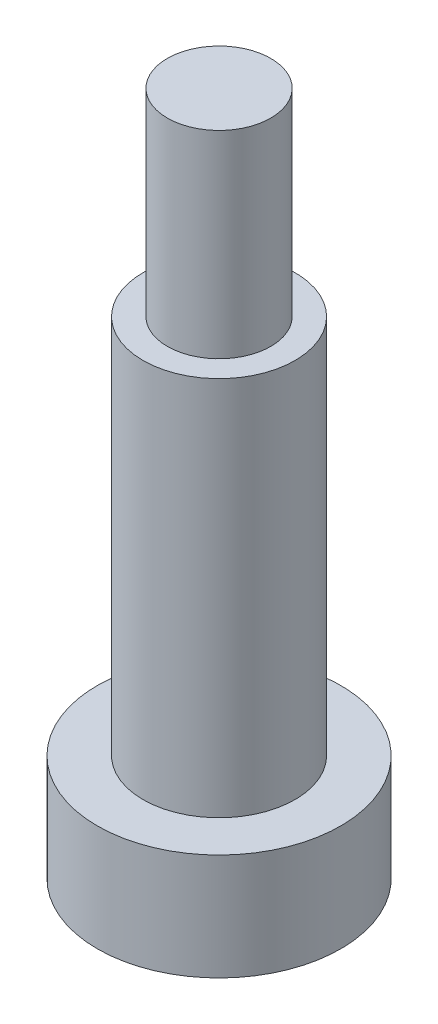
SolidWorks part; units mm, degrees
material "Acero aleado"
ref_plane "Alzado" through (0, 0, 0) normal (0, 0, 1) x (1, 0, 0)
ref_plane "Planta" through (0, 0, 0) normal (0, 1, 0) x (1, 0, 0)
ref_plane "Vista lateral" through (0, 0, 0) normal (1, 0, 0) x (0, 0, -1)
sketch "Croquis1" plane through (0, 0, 0) normal (0, 1, 0) x (1, 0, 0)
  circle A0 centre (152.4, -171.45) radius 3.4
  dimension "D1" = 6.8
  dimension "D2" = 152.4
  dimension "D3" = 171.45
extrude "Rosca" add sketch "Croquis1" along normal blind 13 from offset 3.175
sketch "Croquis2" plane through (0, 0, 0) normal (0, 1, 0) x (1, 0, 0)
  circle A0 centre (152.4, -171.45) radius 5
  dimension "D1" = 10
  dimension "D2" = 152.4
  dimension "D3" = 171.45
extrude "Hombro" add sketch "Croquis2" along normal blind 25 from offset 28.175
sketch "Croquis3" plane through (0, 0, 0) normal (0, 1, 0) x (1, 0, 0)
  circle A0 centre (152.4, -171.45) radius 8
  dimension "D1" = 16
  dimension "D2" = 152.4
  dimension "D3" = 171.45
extrude "Cabeza" add sketch "Croquis3" along normal blind 7 from offset 35.175
sketch "Croquis4" plane through (0, 0, 0) normal (0, 1, 0) x (1, 0, 0)
  circle A0 centre (152.4, -171.45) radius 3.52
  dimension "D1" = 7.04
  dimension "D2" = 152.4
  dimension "D3" = 171.45
extrude "Allen" cut sketch "Croquis4" along normal blind 4.2 from offset 35.175
